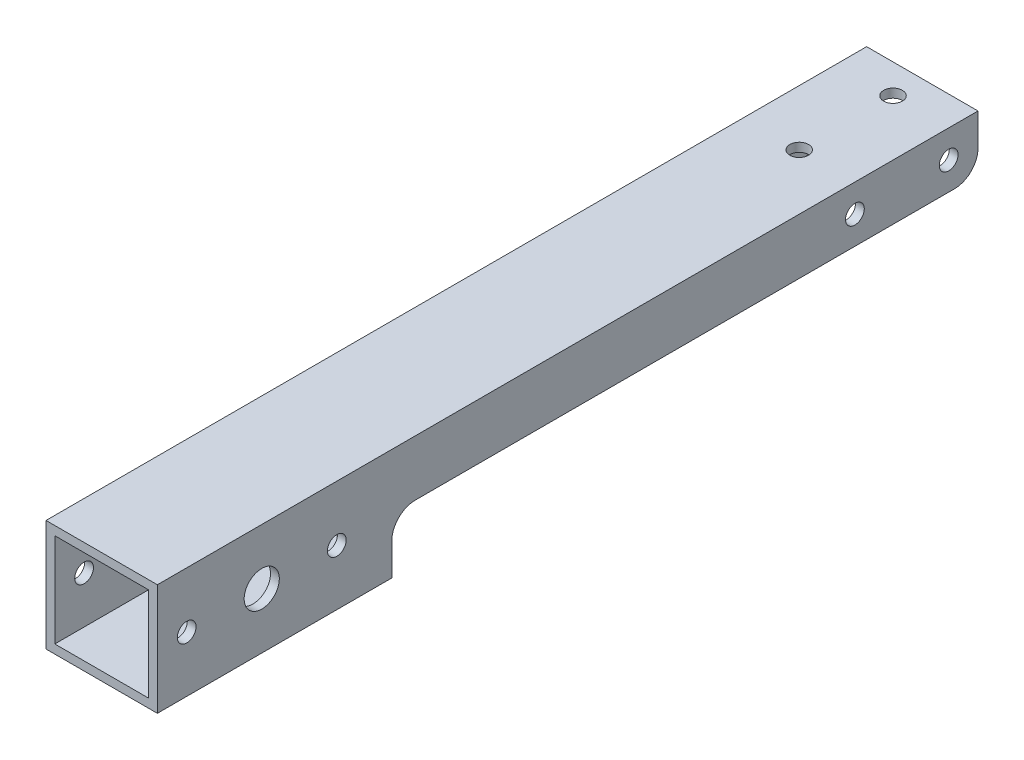
SolidWorks part; units mm, degrees
ref_plane "Plano frontal" through (0, 0, 0) normal (0, 0, 1) x (1, 0, 0)
ref_plane "Plano superior" through (0, 0, 0) normal (0, 1, 0) x (1, 0, 0)
ref_plane "Plano direito" through (0, 0, 0) normal (1, 0, 0) x (0, 0, -1)
sketch "Esboço1" plane through (0, 0, 0) normal (0, 0, 1) x (1, 0, 0)
  line L1 (-9.5, -9.5) -> (9.5, -9.5)
  line L2 (-9.5, -9.5) -> (-9.5, 9.5)
  line L3 (-9.5, 9.5) -> (9.5, 9.5)
  line L4 (9.5, -9.5) -> (9.5, 9.5)
  line L5 (0, 9.5) -> (0, -9.5) construction
  line L6 (-9.5, 0) -> (9.5, 0) construction
  line L7 (8, -8) -> (-8, -8)
  line L8 (8, -8) -> (8, 8)
  line L9 (8, 8) -> (-8, 8)
  line L10 (-8, -8) -> (-8, 8)
  line L11 (0, 8) -> (0, -8) construction
  line L12 (8, 0) -> (-8, 0) construction
  point P0 (0, 0)
  point P4 (0, 0)
  dimension "D1" = 19
  dimension "D2" = 1.5
extrude "Ressalto-extrusão1" add sketch "Esboço1" along normal blind 140 contours L3 L4 L1 L2 | L8 L7 L10 L9
sketch "Esboço2" plane through (9.5, 0, 0) normal (1, 0, 0) x (0, 0, -1)
  line L0 (-161.3966, 22.4643) -> (-181.3966, 6.4643) construction
  line L1 (0, -9.5) -> (0, 9.5) construction
  line L2 (-161.3966, 6.4643) -> (-181.3966, 6.4643) construction
  line L3 (-161.3966, 6.4643) -> (-161.3966, 22.4643) construction
  line L4 (-161.3966, 22.4643) -> (-181.3966, 22.4643) construction
  line L5 (-181.3966, 6.4643) -> (-181.3966, 22.4643) construction
  line L6 (-171.3966, 22.4643) -> (-171.3966, 6.4643) construction
  line L7 (-161.3966, 14.4643) -> (-181.3966, 14.4643) construction
  line L8 (-135, 0) -> (-109.3875, 0) construction
  line L9 (-140, -9.5) -> (-140, 9.5) construction
  line L10 (-12.0679, 0) -> (-12.0679, 9.5) construction
  line L11 (-140, 9.5) -> (0, 9.5) construction
  circle A5 centre (-135, 0) radius 1.6
  circle A6 centre (-122.1938, 0) radius 3
  circle A7 centre (-109.3875, 0) radius 1.6
  circle A8 centre (-5, 4.75) radius 1.6
  circle A9 centre (-21, 4.75) radius 1.6
  point P6 (-171.3966, 14.4643)
  point P13 (-140, 0)
  point P17 (0, 0)
  point P24 (-12.0679, 4.75)
  point P25 (0, 0)
  dimension "D1" = 6
  dimension "D5" = 3.2
  dimension "D8" = 3.2
  dimension "D2" = 16
  dimension "D3" = 20
  dimension "D4" = 5
  dimension "D6" = 16
  dimension "D7" = 5
extrude "Corte-extrusão1" cut sketch "Esboço2" against normal through all contours A7 | A5 | A6 | A8 | A9
sketch "Esboço3" plane through (0, 9.5, 0) normal (0, 1, 0) x (1, 0, 0)
  line L0 (0, -21) -> (0, -5) construction
  line L1 (-9.5, 0) -> (9.5, 0) construction
  circle A1 centre (0, -21) radius 1.6
  circle A2 centre (0, -5) radius 1.6
  dimension "D2" = 3.2
  dimension "D1" = 16
  dimension "D4" = 5
extrude "Corte-extrusão2" cut sketch "Esboço3" against normal up to surface (1.5 mm away) up to face at (0, 8, 70)
sketch "Esboço5" plane through (0, 0, 0) normal (0, 0, -1) x (-1, 0, 0)
  line L0 (-9.5, -9.5) -> (-9.5, 9.5) construction
  line L1 (9.5, -9.5) -> (-9.5, -9.5)
  line L2 (9.5, -9.5) -> (9.5, 0)
  line L3 (9.5, 0) -> (-9.5, 0)
  line L4 (-9.5, -9.5) -> (-9.5, 0)
extrude "Corte-extrusão4" cut sketch "Esboço5" against normal offset from surface (100 mm away) 40 up to face at (0, 0, 140)
fillet "Filete1" radius 4 4 edges at (-8.75, 0, 100) (8.75, 0, 100) (-8.75, 0, 0) (8.75, 0, 0)
